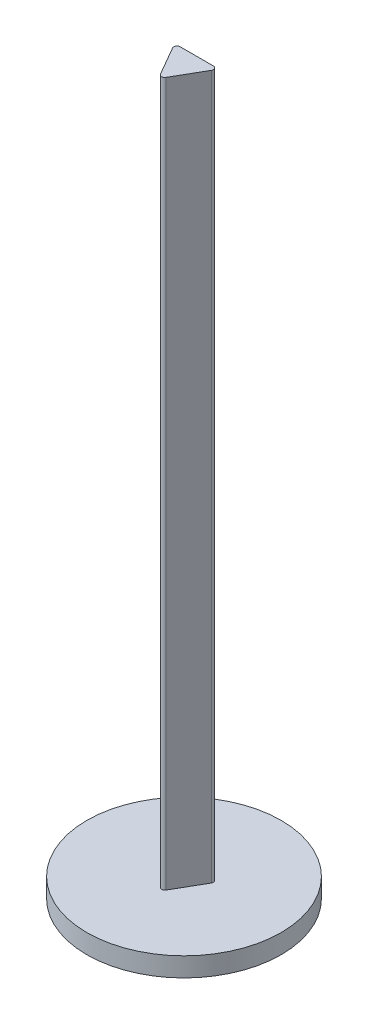
SolidWorks part; units mm, degrees
material "Thornel VCB-20 Carbon Cloth"
ref_plane "Front Plane" through (0, 0, 0) normal (0, 0, 1) x (1, 0, 0)
ref_plane "Top Plane" through (0, 0, 0) normal (0, 1, 0) x (1, 0, 0)
ref_plane "Right Plane" through (0, 0, 0) normal (1, 0, 0) x (0, 0, -1)
sketch "Sketch1" plane through (0, 0, 0) normal (0, 1, 0) x (1, 0, 0)
  circle A0 centre (0, 0) radius 15.19
  dimension "D1" = 30.38
extrude "Boss-Extrude1" add sketch "Sketch1" along normal blind 3
sketch "Sketch2" plane through (0, 3, 0) normal (0, 1, 0) x (1, 0, 0)
  line L1 (0.433, -3.25) -> (3.0311, 1.25)
  line L2 (2.5981, 2) -> (-2.5981, 2)
  line L3 (-3.0311, 1.25) -> (-0.433, -3.25)
  circle A0 centre (0, 0) radius 2 construction
  arc A1 (0.433, -3.25) -> (-0.433, -3.25) centre (0, -3) cw
  arc A2 (3.0311, 1.25) -> (2.5981, 2) centre (2.5981, 1.5) ccw
  arc A3 (-2.5981, 2) -> (-3.0311, 1.25) centre (-2.5981, 1.5) ccw
  dimension "D1" = 0.5
extrude "Boss-Extrude2" add sketch "Sketch2" along normal blind 110
